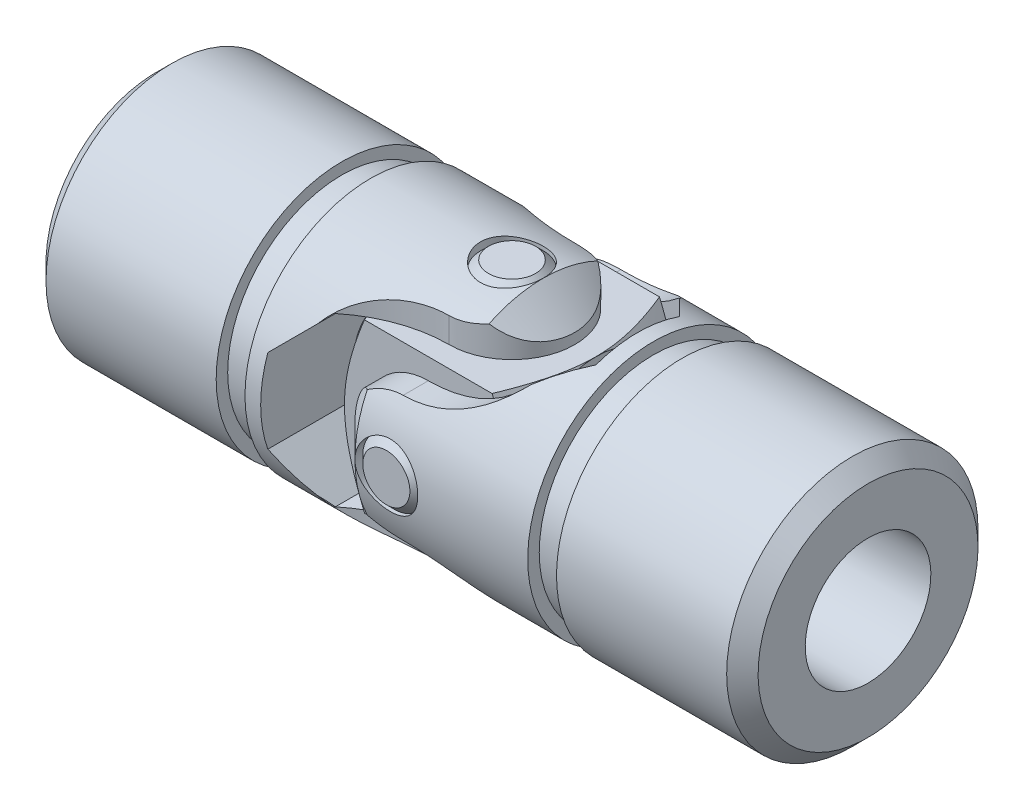
SolidWorks part; units mm, degrees
ref_plane "Front Plane" through (0, 0, 0) normal (0, 0, 1) x (1, 0, 0)
ref_plane "Top Plane" through (0, 0, 0) normal (0, 1, 0) x (1, 0, 0)
ref_plane "Right Plane" through (0, 0, 0) normal (1, 0, 0) x (0, 0, -1)
sketch "Sketch0" plane through (0, 0, 0) normal (0, 1, 0) x (1, 0, 0)
  line L0 (-53.975, 0) -> (53.975, 0) construction
  line L1 (-53.975, 19.05) -> (-53.975, -19.05) construction
  line L2 (-23.8125, 9.525) -> (-23.8125, -9.525) construction
  line L3 (-23.8125, 9.525) -> (-14.2875, 0) construction
  line L4 (-14.2875, 0) -> (-23.8125, -9.525) construction
  line L5 (-19.05, 4.7625) -> (-19.05, -4.7625) construction
  point P7 (-23.8125, 0)
  point P8 (0, 0)
  point P12 (-19.05, 0)
sketch "Sketch1" plane through (0, 0, 0) normal (0, 1, 0) x (1, 0, 0)
  line L0 (-53.975, 19.05) -> (-25.7969, 19.05)
  line L1 (9.525, 19.05) -> (9.525, 0)
  line L2 (9.525, 0) -> (-53.975, 0)
  line L3 (-53.975, 0) -> (-53.975, 19.05)
  line L4 (-53.975, 19.05) -> (-53.975, -19.05) construction
  line L5 (-53.975, 0) -> (53.975, 0) construction
  line L6 (-21.4312, 19.05) -> (9.525, 19.05)
  line L7 (-21.4312, 4.7625) -> (-21.4312, 17.3038) construction
  line L8 (-25.7969, 19.05) -> (-25.7969, 17.3038)
  line L9 (-25.7969, 17.3038) -> (-21.4312, 17.3038)
  line L10 (-21.4312, 19.05) -> (-21.4312, 17.3038)
  line L11 (0, 0) -> (19.05, 0) construction
  line L12 (-19.05, 4.7625) -> (-23.8125, 4.7625) construction
  line L13 (-23.8125, 9.525) -> (-23.8125, -9.525) construction
  circle A0 centre (0, 0) radius 19.05 construction
  dimension "D1" = 4.3656
  dimension "D2" = 1.7462
  dimension "D3" = 63.5
revolve "Revolve1" add sketch "Sketch1" angle 360 about L0
chamfer "Chamfer1" distance 2.3813 angle 45 1 edges at (-53.975, 0, 19.05)
chamfer "Chamfer2" distance 4.7625 angle 45 1 edges at (9.525, 0, 19.05)
sketch "Sketch2" plane through (0, 0, 0) normal (0, 1, 0) x (1, 0, 0)
  line L0 (-21.4312, 19.05) -> (-17.0656, 19.05) construction
  line L1 (-21.4312, 19.05) -> (9.525, 19.05) construction
  line L2 (4.7625, 19.05) -> (-21.4312, 19.05) construction
  line L3 (-25.7969, 17.3038) -> (-21.4312, 17.3038) construction
  line L4 (-53.975, 0) -> (9.525, 0) construction
  line L5 (-17.0656, 19.05) -> (19.05, 19.05)
  line L6 (19.05, 19.05) -> (19.05, -19.05)
  line L7 (19.05, -19.05) -> (-17.0656, -19.05)
  line L8 (0, 9.525) -> (0, 0) construction
  arc A0 (-17.0656, 19.05) -> (0, 9.525) centre (0, 29.5755) ccw
  arc A1 (0, -9.525) -> (0, 9.525) centre (0, 0) ccw
  arc A2 (-17.0656, -19.05) -> (0, -9.525) centre (0, -29.5755) cw
  dimension "D1" = 19.05
extrude "Extrude1" cut sketch "Sketch2" against normal through all and the other way through all
sketch "Sketch3" plane through (0, 0, 0) normal (0, 0, 1) x (1, 0, 0)
  line L0 (-12.7063, 12.6873) -> (-19.05, 6.3437)
  line L1 (-12.7063, 12.6873) -> (19.05, 12.6873)
  line L2 (-19.05, 6.3437) -> (-19.05, -6.3437)
  line L3 (-12.7063, -12.6873) -> (19.05, -12.6873)
  line L4 (19.05, 12.6873) -> (19.05, -12.6873)
  line L5 (-19.05, -6.3437) -> (-12.7063, -12.6873)
  dimension "D1" = 25.3746
  dimension "D2" = 6.3437
extrude "Extrude3" cut sketch "Sketch3" against normal through all and the other way through all
sketch "Sketch4" plane through (-53.975, 0, 0) normal (-1, 0, 0) x (0, 0, 1)
  circle A0 centre (0, 0) radius 9.525
extrude "Extrude4" cut sketch "Sketch4" against normal up to vertex (30.1625 mm away) up to point (-23.8125, 0, -9.525)
sketch "Sketch5" plane through (-23.8125, 0, 0) normal (-1, 0, 0) x (0, 0, 1)
  circle A0 centre (0, 0) radius 9.525 construction
  circle A1 centre (0, 0) radius 9.525
extrude "Extrude5" cut sketch "Sketch5" against normal through all draft 45
sketch "Sketch6" plane through (0, 0, 0) normal (0, 1, 0) x (1, 0, 0)
  line L0 (-53.975, 0) -> (53.975, 0) construction
  line L1 (9.525, 0) -> (4.7625, 0) construction
  line L2 (4.7625, 0) -> (0, 0) construction
  circle A0 centre (0, 0) radius 4.7625
  arc A1 (0, -9.525) -> (0, 9.525) centre (0, 0) ccw construction
  dimension "D1" = 9.525
extrude "Extrude6" cut sketch "Sketch6" against normal through all and the other way through all
mirror "Mirror1" about plane through (0, 0, 0) normal (1, 0, 0) of bodies 109 122
move or copy body "Body-Move/Copy1" bodies to move or copy 110 copy no rotation origin (0, 0, 0) rotation axis (1, 0, 0) rotation angle 90
sketch "Sketch18" plane through (0, 0, 0) normal (0, 1, 0) x (1, 0, 0)
  line L0 (-47.625, -9.525) -> (-23.8125, -9.525)
  line L3 (-47.625, 9.525) -> (-23.8125, 9.525)
  line L4 (-23.8125, 9.525) -> (-23.8125, -9.525)
  line L5 (23.8125, 9.525) -> (23.8125, -9.525)
  line L6 (23.8125, -9.525) -> (53.975, -9.525)
  line L7 (23.8125, 9.525) -> (53.975, 9.525)
  line L8 (0, 0) -> (23.8125, 0) construction
  line L9 (53.975, -16.6687) -> (53.975, 16.6687) construction
  line L11 (-23.8125, -9.525) -> (-23.8125, 9.525) construction
sketch "Sketch10" plane through (0, 0, 0) normal (0, 0, 1) x (1, 0, 0)
  line L0 (-12.7063, 12.6873) -> (12.7064, -12.6873) construction
  line L1 (-12.7063, 12.6873) -> (12.7063, 12.6873)
  line L2 (-12.7063, 12.6873) -> (-12.7063, -12.6873)
  line L3 (-12.7063, -12.6873) -> (12.7064, -12.6873)
  line L4 (12.7063, 12.6873) -> (12.7064, -12.6873)
  line L5 (0, 12.6873) -> (9.525, 12.6873) construction
extrude "Extrude10" add sketch "Sketch10" against normal up to surface and the other way up to surface separate body up to face at (0, 4.7625, -12.6873) other way up to face at (0, -4.7625, 12.6873)
sketch "Sketch11" plane through (12.7063, 0, 0) normal (1, 0, 0) x (0, 0, -1)
  line L4 (-12.6873, -12.6873) -> (-12.6873, 12.6873) construction
  circle A0 centre (0, 0) radius 12.6873
extrude "Extrude11" cut sketch "Sketch11" against normal through all draft 60 flip side to cut
sketch "Sketch12" plane through (-12.7063, -21.0185, 0) normal (1, 0, 0) x (0, -1, 0)
  circle A2 centre (-21.0185, 0) radius 12.6873
  circle A6 centre (-21.0185, 0) radius 12.6873
  dimension "D1" = 0
extrude "Extrude12" cut sketch "Sketch12" along normal through all draft 60 flip side to cut
sketch "Sketch13" plane through (0, 0, 0) normal (0, 1, 0) x (1, 0, 0)
  circle A0 centre (0, 0) radius 4.7625 construction
  circle A1 centre (0, 0) radius 4.7625
extrude "Extrude13" cut sketch "Sketch13" against normal through all and the other way through all
sketch "Sketch14" plane through (0, 0, 0) normal (0, 1, 0) x (1, 0, 0)
  circle A1 centre (0, 0) radius 4.7625
  circle A2 centre (0, 0) radius 4.7625
  dimension "D1" = 0
extrude "Extrude14" add sketch "Sketch14" along normal mid plane 38.1 separate body
sketch "Sketch15" plane through (0, 0, 0) normal (0, 0, 1) x (1, 0, 0)
  circle A0 centre (0, 0) radius 4.7625 construction
  circle A1 centre (0, 0) radius 4.7625
extrude "Extrude15" cut sketch "Sketch15" against normal through all and the other way through all
sketch "Sketch16" plane through (0, 0, 0) normal (0, 0, 1) x (1, 0, 0)
  circle A1 centre (0, 0) radius 4.7625
  circle A2 centre (0, 0) radius 4.7625
  dimension "D1" = 0
extrude "Extrude16" add sketch "Sketch16" along normal mid plane 38.1
chamfer "Chamfer3" distance 1.1906 angle 45 4 edges at (0, -19.05, 4.7625) (0, 19.05, 4.7625) (4.7625, 0, 19.05) (4.7625, 0, -19.05)
move or copy body "Body-Move/Copy2" [suppressed] bodies to move or copy 111 copy no rotation origin (0, 0, 0) rotation axis (0, 0, -1) rotation angle 25
equation "\"D2@Sketch3\" = \"D1@Sketch3\" / 4"
equation "\"D1@Extrude14\" = \"OD@Sketch0\""
equation "\"D1@Extrude16\" = \"D1@Extrude14\""
equation "\"D1@Sketch3\" = \"OD@Sketch0\"*.666"
equation "\"D2@Sketch3\" = \"D1@Sketch3\"/4"
equation "\"D1@Sketch1\" = \"D3@Sketch1\"*.06875"
equation "\"D2@Sketch1\" = \"D1@Sketch1\"/2.5"
equation "\"D1@Chamfer1\" = \"OD@Sketch0\"/16"
equation "\"D1@Chamfer2\" = \"D1@Chamfer1\"*2"
equation "\"D1@Chamfer3\" = \"D1@Chamfer1\"*.50"
